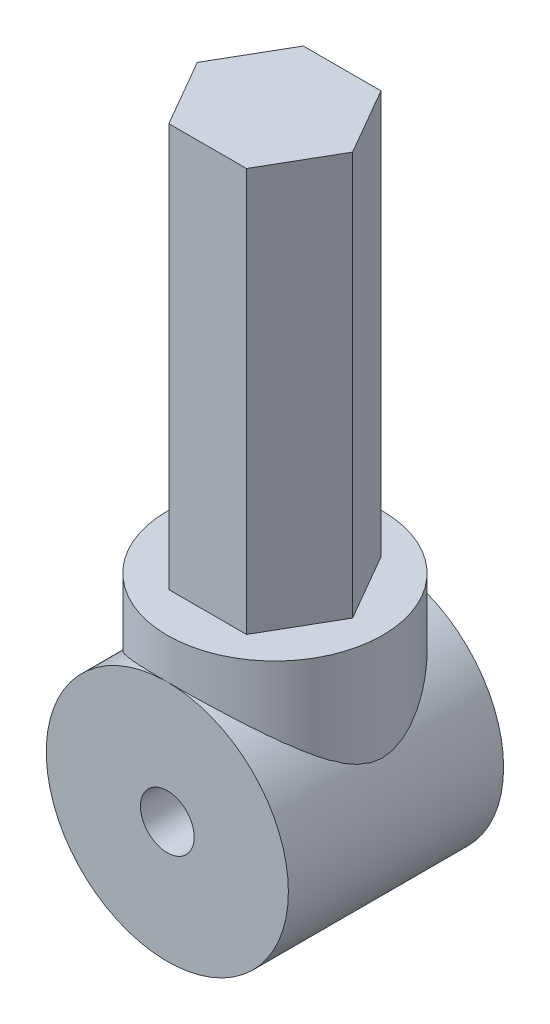
SolidWorks part; units mm, degrees
ref_plane "Front Plane" through (0, 0, 0) normal (0, 0, 1) x (1, 0, 0)
ref_plane "Top Plane" through (0, 0, 0) normal (0, 1, 0) x (1, 0, 0)
ref_plane "Right Plane" through (0, 0, 0) normal (1, 0, 0) x (0, 0, -1)
sketch "Sketch1" plane through (0, 0, 0) normal (0, 0, 1) x (1, 0, 0)
  circle A0 centre (0, 0) radius 5
  circle A1 centre (0, 0) radius 22.5
  dimension "D1" = 10
  dimension "D2" = 45
extrude "Boss-Extrude1" add sketch "Sketch1" along normal blind 40
ref_plane "Plane1" through (0, 5, 0) normal (0, 1, 0) x (1, 0, 0)
sketch "Sketch2" plane through (0, 5, 0) normal (0, 1, 0) x (1, 0, 0)
  line L1 (-22.5, -19.6012) -> (-19.996, -19.6012)
  line L2 (-22.5, 0) -> (-22.5, -40) construction
  line L3 (-20, -20) -> (-22.5, -20)
  circle A0 centre (0, -20) radius 20
  dimension "D3" = 40
extrude "Boss-Extrude2" add sketch "Sketch2" along normal blind 25 separate body contours A0
sketch "Sketch3" plane through (0, 30, 0) normal (0, 1, 0) x (1, 0, 0)
  line L0 (0, 0) -> (0, -20)
  line L1 (0, -20) -> (20, -20)
  line L3 (14.4338, -20) -> (7.2169, -7.5)
  line L4 (7.2169, -7.5) -> (-7.2169, -7.5)
  line L5 (-7.2169, -7.5) -> (-14.4338, -20)
  line L6 (-14.4338, -20) -> (-7.2169, -32.5)
  line L7 (-7.2169, -32.5) -> (7.2169, -32.5)
  line L8 (7.2169, -32.5) -> (14.4338, -20)
  circle A0 centre (0, -20) radius 20 construction
  circle A1 centre (0, -20) radius 12.5 construction
extrude "Boss-Extrude3" add sketch "Sketch3" along normal blind 25 contours L7 L8 L1 L0 L4 L5 L6 | L3 L4 L0 L1
sketch "Sketch4" plane through (0, 55, 0) normal (0, 1, 0) x (1, 0, 0)
  line L1 (7.2169, -32.5) -> (14.4338, -20)
  line L2 (14.4338, -20) -> (7.2169, -7.5)
  line L3 (7.2169, -7.5) -> (-7.2169, -7.5)
  line L4 (-7.2169, -7.5) -> (-14.4338, -20)
  line L5 (-14.4338, -20) -> (-7.2169, -32.5)
  line L6 (-7.2169, -32.5) -> (7.2169, -32.5)
  circle A0 centre (0, -20) radius 12.5 construction
extrude "Boss-Extrude4" add sketch "Sketch4" along normal blind 50
